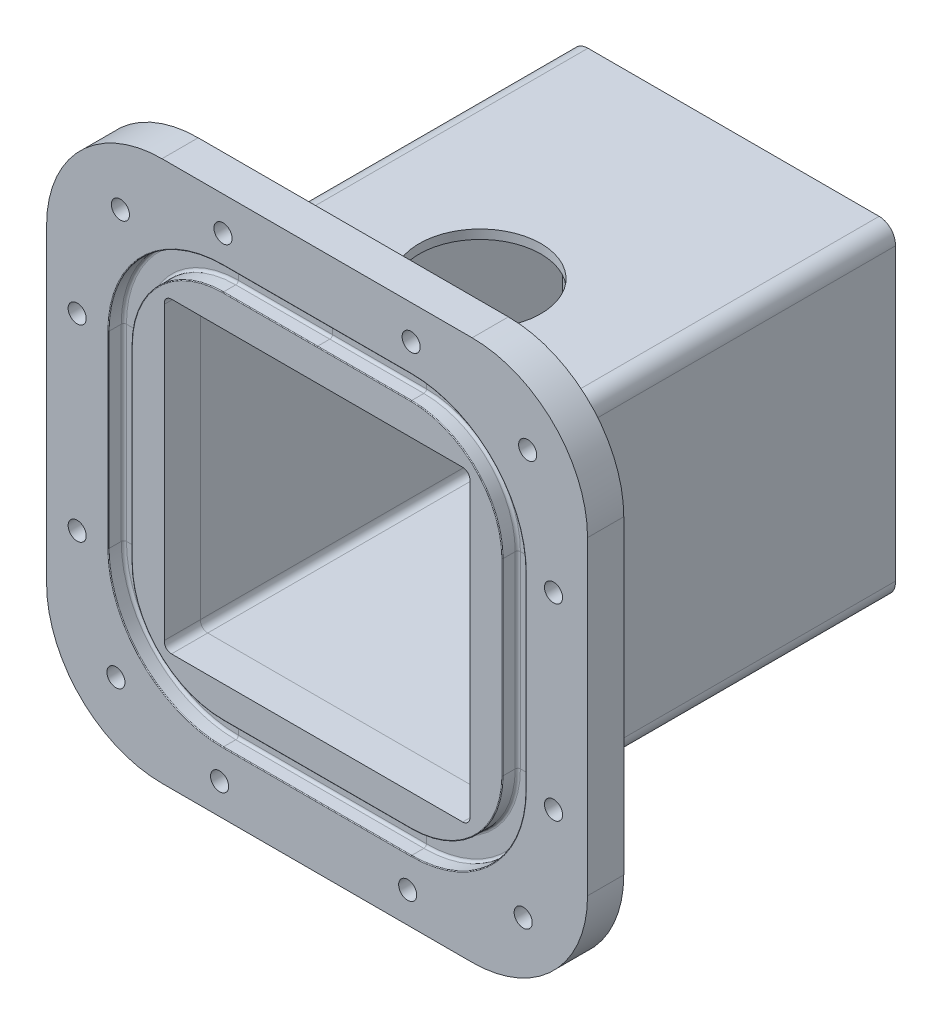
SolidWorks part; units mm, degrees
material "6061 Alloy"
ref_plane "Front Plane" through (0, 0, 0) normal (0, 0, 1) x (1, 0, 0)
ref_plane "Top Plane" through (0, 0, 0) normal (0, 1, 0) x (1, 0, 0)
ref_plane "Right Plane" through (0, 0, 0) normal (1, 0, 0) x (0, 0, -1)
sketch "Sketch1" plane through (0, 0, 0) normal (0, 0, 1) x (1, 0, 0)
  line L103 (-25.5249, 26.9353) -> (25.5249, 26.9353)
  line L104 (26.7871, -25.5249) -> (26.7871, 25.5249)
  line L108 (0, 26.9353) -> (0, -26.9353) construction
  line L113 (26.7871, 0) -> (-26.7871, 0) construction
  line L114 (-25.5249, -26.9353) -> (25.5249, -26.9353)
  line L115 (-26.7871, -25.5249) -> (-26.7871, 25.5249)
  line L116 (-25.5249, 28.5228) -> (25.5249, 28.5228)
  line L117 (28.3746, -25.4545) -> (28.3746, 25.4545)
  line L118 (-25.5249, -28.5228) -> (25.5249, -28.5228)
  line L119 (-28.3746, -25.4545) -> (-28.3746, 25.4545)
  arc A86 (-26.7871, 25.5249) -> (-25.5249, 26.9353) centre (-25.5249, 25.6653) cw
  arc A87 (25.5249, 26.9353) -> (26.7871, 25.5249) centre (25.5249, 25.6653) cw
  arc A88 (26.7871, -25.5249) -> (25.5249, -26.9353) centre (25.5249, -25.6653) cw
  arc A89 (-25.5249, -26.9353) -> (-26.7871, -25.5249) centre (-25.5249, -25.6653) cw
  arc A90 (25.5249, 28.5228) -> (28.3746, 25.4545) centre (25.5249, 25.6653) cw
  arc A91 (28.3746, -25.4545) -> (25.5249, -28.5228) centre (25.5249, -25.6653) cw
  arc A92 (-25.5249, -28.5228) -> (-28.3746, -25.4545) centre (-25.5249, -25.6653) cw
  arc A93 (-28.3746, 25.4545) -> (-25.5249, 28.5228) centre (-25.5249, 25.6653) cw
  point P2 (0, 0)
  point P8 (-26.4713, 26.5122)
  point P9 (26.4713, -26.5122)
  point P16 (0, 0)
  point P17 (0, 0)
  point P29 (0, 0)
  point P32 (0, 0)
  point P33 (0, 0)
  point P42 (0, 0)
  point P82 (0, 0)
  point P89 (0, 0)
  point P140 (0, 0)
  dimension "D1" = 1.5875
  dimension "D3" = 74.93
  dimension "D6" = 1.27
extrude "Boss-Extrude1" add sketch "Sketch1" against normal blind 63.5
sketch "Sketch12" plane through (0, 0, 0) normal (0, 0, 1) x (1, 0, 0)
  line L16 (-28.3746, 25.4545) -> (-28.3746, -25.4545)
  line L17 (-25.5249, -28.5228) -> (25.5249, -28.5228)
  line L18 (28.3746, -25.4545) -> (28.3746, 25.4545)
  line L19 (25.5249, 28.5228) -> (-25.5249, 28.5228)
  line L20 (-28.3746, 25.4545) -> (-28.3746, -25.4545)
  line L21 (-25.5249, -28.5228) -> (25.5249, -28.5228)
  line L22 (28.3746, -25.4545) -> (28.3746, 25.4545)
  line L23 (25.5249, 28.5228) -> (-25.5249, 28.5228)
  circle A8 centre (0, 0) radius 12.5
  arc A17 (-25.5249, 28.5228) -> (-28.3746, 25.4545) centre (-25.5249, 25.6653) ccw
  arc A18 (-28.3746, -25.4545) -> (-25.5249, -28.5228) centre (-25.5249, -25.6653) ccw
  arc A19 (25.5249, -28.5228) -> (28.3746, -25.4545) centre (25.5249, -25.6653) ccw
  arc A20 (28.3746, 25.4545) -> (25.5249, 28.5228) centre (25.5249, 25.6653) ccw
  arc A21 (-25.5249, 28.5228) -> (-28.3746, 25.4545) centre (-25.5249, 25.6653) ccw
  arc A22 (-28.3746, -25.4545) -> (-25.5249, -28.5228) centre (-25.5249, -25.6653) ccw
  arc A23 (25.5249, -28.5228) -> (28.3746, -25.4545) centre (25.5249, -25.6653) ccw
  arc A24 (28.3746, 25.4545) -> (25.5249, 28.5228) centre (25.5249, 25.6653) ccw
  dimension "D1" = 25
  dimension "D2" = 0
extrude "Boss-Extrude2" add sketch "Sketch12" against normal blind 3.175 from surface at -63.5
sketch "Sketch18" plane through (0, 0, 0) normal (0, 1, 0) x (1, 0, 0)
  line L1 (25.5249, 66.675) -> (-25.5249, 66.675) construction
  circle A0 centre (0, 22.225) radius 10.668
  dimension "D1" = 21.336
  dimension "D2" = 44.45
extrude "Cut-Extrude6" cut sketch "Sketch18" against normal up to next (26.9353 mm away) and the other way through all from surface at 28.5228 starting at face at (0, 28.5228, -33.3375)
sketch "Sketch19" plane through (0, 0, 0) normal (0, 0, 1) x (1, 0, 0)
  line L0 (28.3746, -25.4545) -> (28.3746, 25.4545) construction
  line L1 (-27.1935, -47.4246) -> (27.1935, -47.4246)
  line L2 (-47.4246, -27.1935) -> (-47.4246, 27.1935)
  line L3 (-27.1935, 47.4246) -> (27.1935, 47.4246)
  line L4 (47.4246, -27.1935) -> (47.4246, 27.1935)
  line L5 (-47.4246, -47.4246) -> (47.4246, 47.4246) construction
  line L6 (-47.4246, 47.4246) -> (47.4246, -47.4246) construction
  line L14 (26.7871, -25.5249) -> (26.7871, 25.5249) construction
  line L15 (-25.5249, -26.9353) -> (25.5249, -26.9353) construction
  line L16 (-26.7871, -25.5249) -> (-26.7871, 25.5249) construction
  line L17 (-25.5249, 26.9353) -> (25.5249, 26.9353) construction
  line L18 (26.7871, -25.5249) -> (26.7871, 25.5249)
  line L19 (-25.5249, -26.9353) -> (25.5249, -26.9353)
  line L20 (-26.7871, -25.5249) -> (-26.7871, 25.5249)
  line L21 (-25.5249, 26.9353) -> (25.5249, 26.9353)
  arc A0 (27.1935, 47.4246) -> (47.4246, 27.1935) centre (27.1935, 27.1935) cw
  arc A1 (47.4246, -27.1935) -> (27.1935, -47.4246) centre (27.1935, -27.1935) cw
  arc A2 (-27.1935, -47.4246) -> (-47.4246, -27.1935) centre (-27.1935, -27.1935) cw
  arc A3 (-47.4246, 27.1935) -> (-27.1935, 47.4246) centre (-27.1935, 27.1935) cw
  arc A12 (25.5249, -26.9353) -> (26.7871, -25.5249) centre (25.5249, -25.6653) ccw construction
  arc A13 (-26.7871, -25.5249) -> (-25.5249, -26.9353) centre (-25.5249, -25.6653) ccw construction
  arc A14 (-25.5249, 26.9353) -> (-26.7871, 25.5249) centre (-25.5249, 25.6653) ccw construction
  arc A15 (26.7871, 25.5249) -> (25.5249, 26.9353) centre (25.5249, 25.6653) ccw construction
  arc A16 (25.5249, -26.9353) -> (26.7871, -25.5249) centre (25.5249, -25.6653) ccw
  arc A17 (-26.7871, -25.5249) -> (-25.5249, -26.9353) centre (-25.5249, -25.6653) ccw
  arc A18 (-25.5249, 26.9353) -> (-26.7871, 25.5249) centre (-25.5249, 25.6653) ccw
  arc A19 (26.7871, 25.5249) -> (25.5249, 26.9353) centre (25.5249, 25.6653) ccw
  point P0 (0, 0)
  dimension "D3" = 20.2311
  dimension "D1" = 19.05
extrude "Boss-Extrude3" add sketch "Sketch19" along normal blind 6.35 separate body
sketch "Sketch11" plane through (0, 0, 6.35) normal (0, 0, 1) x (1, 0, 0)
  line L0 (0, 32.3799) -> (0, -32.3799) construction
  line L1 (-16.4922, -32.3799) -> (16.4922, -32.3799)
  line L2 (-32.3799, -16.4922) -> (-32.3799, 16.4922)
  line L3 (-16.4922, 32.3799) -> (16.4922, 32.3799)
  line L4 (32.3799, -16.4922) -> (32.3799, 16.4922)
  line L5 (32.3799, 0) -> (-32.3799, 0) construction
  arc A0 (16.4922, 32.3799) -> (32.3799, 16.4922) centre (16.4922, 16.4922) cw
  arc A1 (32.3799, -16.4922) -> (16.4922, -32.3799) centre (16.4922, -16.4922) cw
  arc A2 (-16.4922, -32.3799) -> (-32.3799, -16.4922) centre (-16.4922, -16.4922) cw
  arc A3 (-32.3799, 16.4922) -> (-16.4922, 32.3799) centre (-16.4922, 16.4922) cw
  point P0 (0, 0)
  point P23 (0, 0)
  dimension "D1" = 15.8877
  dimension "D2" = 231.7633
sketch "Sketch17" plane through (0, 0, 0) normal (1, 0, 0) x (0, 0, -1)
  line L0 (-6.223, 32.5069) -> (-4.1148, 32.5069)
  line L1 (-3.6576, 32.9641) -> (-3.6576, 36.1137)
  line L2 (-4.1148, 36.5709) -> (-6.223, 36.5709)
  line L3 (-6.35, 32.3799) -> (-6.35, 36.6979)
  line L4 (-6.35, 34.5389) -> (-3.6576, 34.5389) construction
  arc A0 (-6.223, 36.5709) -> (-6.35, 36.6979) centre (-6.223, 36.6979) cw
  arc A1 (-6.223, 32.5069) -> (-6.35, 32.3799) centre (-6.223, 32.3799) ccw
  arc A2 (-3.6576, 36.1137) -> (-4.1148, 36.5709) centre (-4.1148, 36.1137) ccw
  arc A3 (-3.6576, 32.9641) -> (-4.1148, 32.5069) centre (-4.1148, 32.9641) cw
  dimension "D1" = 0.127
  dimension "D2" = 0.4572
  dimension "D3" = 4.064
  dimension "D4" = 2.6924
sweep "Cut-Sweep1" cut profiles "Sketch17" path "Sketch11"
sketch "Sketch10" plane through (0, 0, 0) normal (0, 0, 1) x (1, 0, 0)
  line L0 (30.7798, -30.7798) -> (41.4991, -41.4991) construction
  line L1 (-36.6979, 16.4922) -> (-47.4246, 16.4922) construction
  line L2 (-47.4246, 27.1935) -> (-47.4246, -27.1935) construction
  line L3 (-36.6979, -16.4922) -> (-47.4246, -16.4922) construction
  circle A0 centre (-35.263, -35.3529) radius 1.5875
  circle A1 centre (-34.4765, 36.0495) radius 1.5875
  circle A2 centre (36.926, 35.263) radius 1.5875
  circle A3 centre (-42.0613, -16.4922) radius 1.5875
  circle A5 centre (36.1394, -36.1394) radius 1.5875
  arc A8 (16.4922, -36.6979) -> (36.6979, -16.4922) centre (16.4922, -16.4922) ccw construction
  arc A9 (27.1935, -47.4246) -> (47.4246, -27.1935) centre (27.1935, -27.1935) ccw construction
  circle A10 centre (-42.0613, 16.4922) radius 1.5875
  circle A11 centre (16.4922, 41.4607) radius 1.5875
  circle A12 centre (-16.4922, 41.4607) radius 1.5875
  circle A13 centre (41.4607, -17.0928) radius 1.5875
  circle A14 centre (41.4607, 15.8917) radius 1.5875
  circle A15 centre (-17.0928, -42.0613) radius 1.5875
  circle A16 centre (15.8917, -42.0613) radius 1.5875
  point P12 (36.1394, -36.1394)
  point P20 (0.8315, -0.045)
  point P46 (-0.3003, -0.3003)
  dimension "D1" = 3.175
  dimension "D2" = 4
extrude "Cut-Extrude7" cut sketch "Sketch10" against normal up to next (63.5 mm away) from surface at 6.35 starting at face at (0, 0, 6.35)
sketch "Sketch14" [suppressed] plane through (37.5777, 0, 0) normal (1, 0, 0) x (0, 0, -1)
  line L0 (63.5, 36.784) -> (63.5, -36.784) construction
  line L1 (63.5, 37.5777) -> (0, 37.5777) construction
  line L2 (63.5, -37.5777) -> (0, -37.5777) construction
  circle A0 centre (50.8, 33.0057) radius 1.5875
  circle A1 centre (50.8, -33.0057) radius 1.5875
  dimension "D3" = 3.175
  dimension "D4" = 3.175
  dimension "D1" = 12.7
  dimension "D2" = 12.7
  dimension "D5" = 4.572
  dimension "D6" = 4.572
extrude "Cut-Extrude4" [suppressed] cut sketch "Sketch14" against normal blind 6.35
